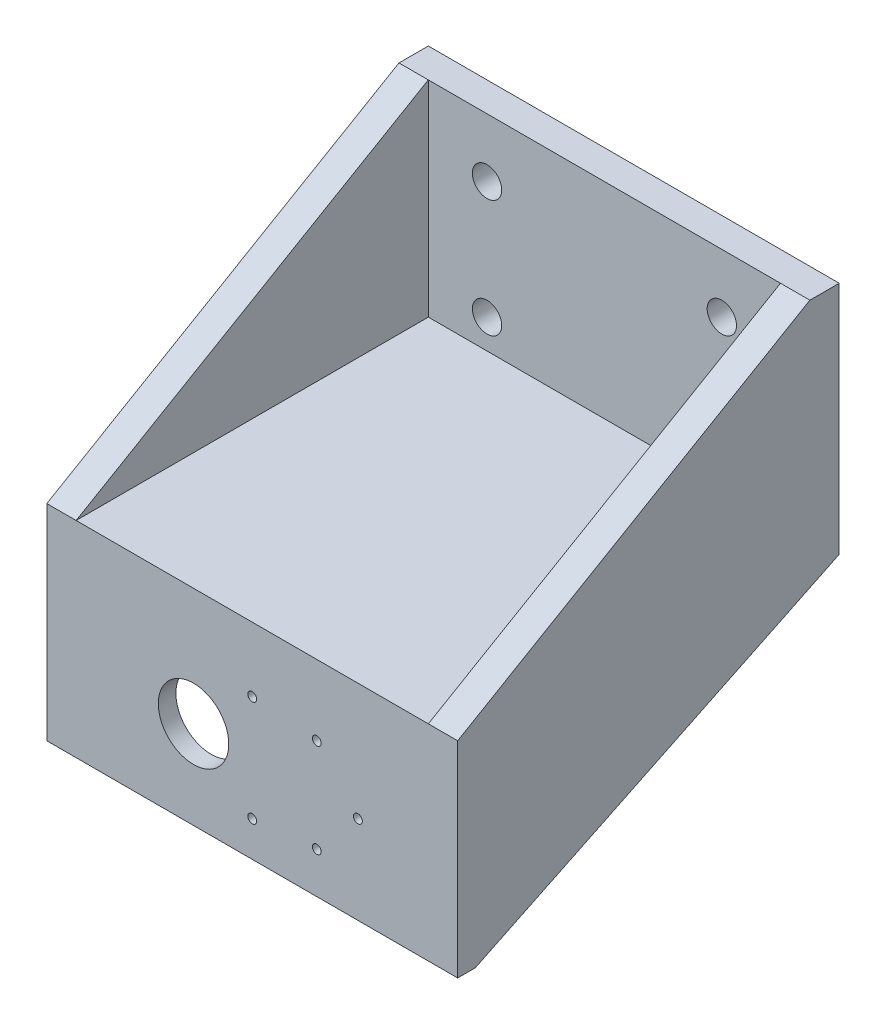
SolidWorks part; units mm, degrees
ref_plane "前视基准面" through (0, 0, 0) normal (0, 0, 1) x (1, 0, 0)
ref_plane "上视基准面" through (0, 0, 0) normal (0, 1, 0) x (1, 0, 0)
ref_plane "右视基准面" through (0, 0, 0) normal (1, 0, 0) x (0, 0, -1)
sketch "草图1" plane through (0, 0, 0) normal (0, 0, 1) x (1, 0, 0)
  line L1 (35, -20) -> (-35, -20)
  line L2 (35, -20) -> (35, 20)
  line L3 (35, 20) -> (-35, 20)
  line L4 (-35, -20) -> (-35, 20)
  line L5 (35, -20) -> (-35, 20) construction
  line L6 (35, 20) -> (-35, -20) construction
  circle A0 centre (-20, 10) radius 2.5
  circle A1 centre (20, 10) radius 2.5
  circle A2 centre (-20, -10) radius 2.5
  circle A3 centre (20, -10) radius 2.5
  point P0 (0, 0)
  dimension "D3" = 5
  dimension "D4" = 5
  dimension "D5" = 5
  dimension "D6" = 5
  dimension "D1" = 70
  dimension "D2" = 40
  dimension "D7" = 10
  dimension "D8" = 15
  dimension "D9" = 10
  dimension "D10" = 15
  dimension "D11" = 20
  dimension "D12" = 20
  dimension "D13" = 40
  dimension "D14" = 15
extrude "凸台-拉伸1" add sketch "草图1" along normal blind 5
sketch "草图3" plane through (0, 0, 5) normal (0, 0, 1) x (1, 0, 0)
  line L0 (35, 20) -> (-35, 20) construction
  line L1 (35, -20) -> (-35, -20)
  line L2 (35, -20) -> (35, 20)
  line L3 (35, 20) -> (-35, 20)
  line L4 (-35, -20) -> (-35, 20)
  line L5 (35, -20) -> (-35, 20) construction
  line L6 (35, 20) -> (-35, -20) construction
  line L8 (-30, 20) -> (30, 20)
  line L9 (-30, 20) -> (-30, -15)
  line L10 (-30, -15) -> (30, -15)
  line L11 (30, 20) -> (30, -15)
  point P0 (0, 0)
  line M9 (-35, 20) -> (-35, -20)
  line M10 (-35, -20) -> (35, -20)
  line M11 (35, -20) -> (35, 20)
  line M12 (35, 20) -> (-35, 20)
  dimension "D1" = 5
  dimension "D2" = 5
  dimension "D3" = 5
extrude "凸台-拉伸2" add sketch "草图3" along normal blind 60 contours L11 L10 L9 M12 M9 M10 M11
sketch "草图4" plane through (-35, 0, 0) normal (-1, 0, 0) x (0, 0, 1)
  line L0 (5, 20) -> (65, -15)
  line L1 (65, 20) -> (0, 20) construction
  line L2 (65, 20) -> (65, -20) construction
  line L3 (65, -15) -> (65, 20)
  line L4 (65, 20) -> (5, 20)
  line L5 (0, 20) -> (0, -20) construction
  dimension "D1" = 5
  dimension "D2" = 5
extrude "切除-拉伸1" cut sketch "草图4" against normal blind 100
sketch "草图5" plane through (0, -20, 0) normal (0, -1, 0) x (1, 0, 0)
  line L1 (35, 0) -> (-35, 0)
  line L2 (35, 0) -> (35, 65)
  line L3 (35, 65) -> (-35, 65)
  line L4 (-35, 0) -> (-35, 65)
  line L5 (30, 0) -> (-30, 0)
  line L6 (30, 0) -> (30, 62)
  line L7 (30, 62) -> (-30, 62)
  line L8 (-30, 0) -> (-30, 62)
  line M8 (-35, 0) -> (35, 0)
  line M9 (35, 0) -> (35, 65)
  line M10 (35, 65) -> (-35, 65)
  line M11 (-35, 65) -> (-35, 0)
  dimension "D1" = 5
  dimension "D2" = 5
  dimension "D3" = 3
extrude "凸台-拉伸3" add sketch "草图5" along normal blind 30 contours L8 L7 L6 M8 M9 M10 M11
sketch "草图6" plane through (-35, 0, 0) normal (-1, 0, 0) x (0, 0, 1)
  line L0 (62, -50) -> (0, -20)
  line L1 (65, -50) -> (0, -50) construction
  line L3 (0, -20) -> (0, -50)
  line L4 (0, -50) -> (62, -50)
  line L5 (65, -15) -> (65, -50) construction
  line L6 (0, 20) -> (0, -50) construction
  dimension "D1" = 30
  dimension "D2" = 3
extrude "切除-拉伸2" cut sketch "草图6" against normal blind 70
sketch "草图8" plane through (0, 0, 65) normal (0, 0, 1) x (1, 0, 0)
  line L1 (20, -45) -> (-20, -45) construction
  line L2 (20, -45) -> (20, -25) construction
  line L3 (20, -25) -> (-20, -25) construction
  line L4 (-20, -45) -> (-20, -25) construction
  line L5 (-35, -15) -> (-35, -50) construction
  line L6 (35, -50) -> (-35, -50) construction
  circle A0 centre (-10, -35) radius 6
  circle A1 centre (18, -35) radius 0.75
  circle A2 centre (11, -43) radius 0.75
  circle A3 centre (0, -44) radius 0.75
  circle A4 centre (11, -27) radius 0.75
  circle A5 centre (0, -26) radius 0.75
  dimension "D4" = 10
  dimension "D5" = 12
  dimension "D6" = 1.5
  dimension "D7" = 1.5
  dimension "D8" = 1.5
  dimension "D9" = 1.5
  dimension "D10" = 1.5
  dimension "D1" = 40
  dimension "D2" = 20
  dimension "D3" = 15
  dimension "D11" = 1
  dimension "D12" = 1
  dimension "D13" = 2
  dimension "D14" = 2
  dimension "D15" = 9
  dimension "D16" = 9
  dimension "D17" = 20
  dimension "D18" = 20
  dimension "D19" = 10
  dimension "D20" = 2
  dimension "D21" = 5
  dimension "D22" = 10
extrude "切除-拉伸3" cut sketch "草图8" against normal blind 5
